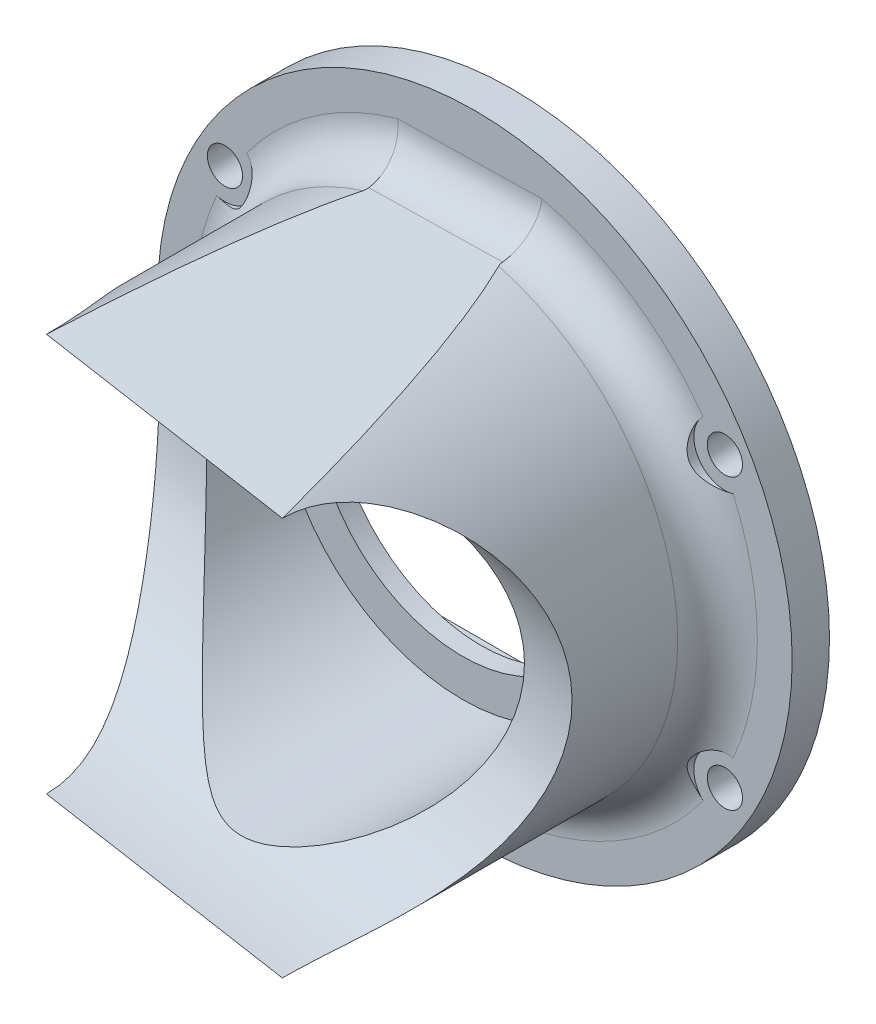
SolidWorks part; units mm, degrees
material "6061-T6 (SS)"
ref_plane "Front Plane" through (0, 0, 0) normal (0, 0, 1) x (1, 0, 0)
ref_plane "Top Plane" through (0, 0, 0) normal (0, 1, 0) x (1, 0, 0)
ref_plane "Right Plane" through (0, 0, 0) normal (1, 0, 0) x (0, 0, -1)
sketch "Sketch1" plane through (0, 0, 0) normal (0, 0, 1) x (1, 0, 0)
  circle A0 centre (0, 0) radius 30.9562
  dimension "D1" = 61.9125
extrude "Boss-Extrude1" add sketch "Sketch1" along normal blind 50.8
sketch "Sketch2" plane through (0, 0, 0) normal (0, 0, -1) x (-1, 0, 0)
  line L1 (-18.3261, -22.2885) -> (18.3261, -22.2885)
  line L2 (-22.2885, -18.3261) -> (-22.2885, 18.3261)
  line L3 (-18.3261, 22.2885) -> (18.3261, 22.2885)
  line L4 (22.2885, -18.3261) -> (22.2885, 18.3261)
  line L5 (-22.2885, -22.2885) -> (22.2885, 22.2885) construction
  line L6 (-22.2885, 22.2885) -> (22.2885, -22.2885) construction
  arc A0 (18.3261, -22.2885) -> (22.2885, -18.3261) centre (18.3261, -18.3261) ccw
  arc A1 (-18.3261, -22.2885) -> (-22.2885, -18.3261) centre (-18.3261, -18.3261) cw
  arc A2 (18.3261, 22.2885) -> (22.2885, 18.3261) centre (18.3261, 18.3261) cw
  arc A3 (-22.2885, 18.3261) -> (-18.3261, 22.2885) centre (-18.3261, 18.3261) cw
  point P0 (0, 0)
  dimension "D3" = 3.9624
  dimension "D1" = 44.577
  dimension "D2" = 44.577
extrude "Cut-Extrude1" cut sketch "Sketch2" against normal blind 3.9624
ref_plane "Plane1" through (30.9562, 0, 0) normal (1, 0, 0) x (0, 0, -1)
sketch "Sketch16" plane through (30.9562, 0, 0) normal (1, 0, 0) x (0, 0, -1)
  line L0 (0, 0) -> (0, -56.7352) construction
ref_plane "Plane4" through (30.2799, 0, 4.5254) normal (0.989, 0, 0.1478) x (0.1478, 0, -0.989)
sketch "Sketch3" plane through (30.9562, 0, 0) normal (0.989, 0, 0.1478) x (0.1478, 0, -0.989)
  line L1 (-48.4676, 25.4) -> (-4.5756, 30.9562)
  line L2 (-4.5756, 30.9562) -> (-67.5176, 30.9562)
  line L3 (-67.5176, 30.9562) -> (-67.5176, -30.9562)
  line L4 (-67.5176, -30.9562) -> (-4.5756, -30.9562)
  line L5 (-4.5756, -30.9562) -> (-48.4676, -25.4)
  arc A0 (-48.4676, -25.4) -> (-48.4676, 25.4) centre (-48.4676, 0) ccw
  dimension "D1" = 50.8
  dimension "D2" = 19.05
  dimension "D3" = 62.942
extrude "Cut-Extrude2" cut sketch "Sketch3" against normal through all and the other way through all
sketch "Sketch4" plane through (0, 0, 3.9624) normal (0, 0, -1) x (-1, 0, 0)
  circle A0 centre (0, 0) radius 19.05
  dimension "D1" = 38.1
extrude "Cut-Extrude3" cut sketch "Sketch4" against normal through all
ref_plane "Plane2" through (0, 0, 50.8) normal (0, 0, 1) x (1, 0, 0)
sketch "Sketch6" plane through (0, 0, 50.8) normal (0, 0, 1) x (1, 0, 0)
  circle A0 centre (0, 0) radius 23.8125
  dimension "D1" = 47.625
extrude "Cut-Extrude4" cut sketch "Sketch6" against normal blind 44.45
sketch "Sketch7" plane through (0, 0, 3.9624) normal (0, 0, -1) x (-1, 0, 0)
  line L1 (-18.2626, -18.2626) -> (18.2626, -18.2626) construction
  line L2 (-18.2626, -18.2626) -> (-18.2626, 18.2626) construction
  line L3 (-18.2626, 18.2626) -> (18.2626, 18.2626) construction
  line L4 (18.2626, -18.2626) -> (18.2626, 18.2626) construction
  line L5 (-18.2626, -18.2626) -> (18.2626, 18.2626) construction
  line L6 (-18.2626, 18.2626) -> (18.2626, -18.2626) construction
  point P0 (0, 0)
  dimension "D1" = 36.5252
  dimension "D2" = 36.5252
hole_wizard "#4-40 Tapped Hole1" positions "Sketch9" profile "Sketch8" tap size "#4-40" standard "Ansi Inch"
sketch "Sketch9" plane through (0, 0, 3.9624) normal (0, 0, -1) x (-1, 0, 0)
  point P0 (-18.2626, 18.2626)
  point P1 (18.2626, 18.2626)
  point P4 (18.2626, -18.2626)
  point P7 (-18.2626, -18.2626)
sketch "Sketch8" plane through (18.2626, 18.2626, 3.9624) normal (1, 0, 0) x (0, 1, 0)
  line L0 (0, 0) -> (0, 8.2992)
  line L1 (0, 8.2992) -> (1.1303, 7.62)
  line L2 (1.1303, 7.62) -> (1.1303, 0)
  line L5 (1.1303, 0) -> (0, 0)
  line L10 (0, 8.2992) -> (-1.1303, 7.62) construction
  line L11 (0, -6.35) -> (0, 107.95) construction
  dimension "Tap Drill Dia." = 2.2606
  dimension "Tap Drill Depth" = 7.62
  dimension "Drill Angle" = 118
cosmetic thread "Hole Thread1" parameters "D1"=5.588, "D2"=2.8448
cosmetic thread "Hole Thread2" parameters "D1"=5.588, "D2"=2.8448
cosmetic thread "Hole Thread3" parameters "D1"=5.588, "D2"=2.8448
cosmetic thread "Hole Thread4" parameters "D1"=5.588, "D2"=2.8448
sketch "Sketch10" plane through (0, 0, 0) normal (0, 0, -1) x (-1, 0, 0)
  line L0 (-17.6955, 25.4) -> (17.6955, 25.4)
  line L1 (-17.6955, -25.4) -> (17.6955, -25.4)
  arc A0 (-17.6955, 25.4) -> (-17.6955, -25.4) centre (0, 0) ccw
  arc A1 (0, 30.9562) -> (0, -30.9562) centre (0, 0) ccw construction
  circle A2 centre (0, 0) radius 40.4813
  arc A3 (17.6955, -25.4) -> (17.6955, 25.4) centre (0, 0) ccw
  dimension "D1" = 9.525
  dimension "D2" = 25.4
extrude "Boss-Extrude3" add sketch "Sketch10" against normal blind 4.7625
sketch "Sketch12" plane through (0, 0, 4.7625) normal (0, 0, 1) x (1, 0, 0)
  circle A0 centre (0, 0) radius 36.83 construction
  dimension "D1" = 73.66
fillet "Fillet1" radius 5.08 4 edges at (30.9562, 0, 4.7625) (-30.9562, 0, 4.7625) (-0.5679, -30.3494, 4.7625) (-0.5679, 30.3494, 4.7625)
hole_wizard "#8 Clearance Hole1" positions "Sketch14" profile "Sketch13" hole size "#8" standard "ANSI Inch"
sketch "Sketch14" plane through (0, 0, 4.7625) normal (0, 0, 1) x (1, 0, 0)
  line L0 (0, 0) -> (0, 40.4813) construction
  line L2 (0, 0) -> (-31.8957, 18.415) construction
  circle A0 centre (0, 0) radius 36.83 construction
  circle A1 centre (0, 0) radius 40.4813 construction
  point P0 (-31.8957, 18.415)
  dimension "D1" = 60
sketch "Sketch13" plane through (-31.8957, 18.415, 4.7625) normal (1, 0, 0) x (0, -1, 0)
  line L0 (0, 0) -> (0, 26.7507)
  line L1 (0, 26.7507) -> (2.2479, 25.4)
  line L2 (2.2479, 25.4) -> (2.2479, 0)
  line L5 (2.2479, 0) -> (0, 0)
  line L10 (0, 26.7507) -> (-2.2479, 25.4) construction
  line L11 (0, -6.35) -> (0, 107.95) construction
  dimension "Hole Dia." = 4.4958
  dimension "Hole Depth" = 25.4
  dimension "Drill Angle" = 118
pattern_circular "CirPattern1" count 2 every 120 about axis through (0, 0, 4.7625) along (0, 0, -1) of "#8 Clearance Hole1"
ref_plane "Plane3" through (0, 0, 9.8425) normal (0, 0, 1) x (1, 0, 0)
mirror "Mirror1" about plane through (0, 0, 0) normal (0, 1, 0) of "CirPattern1", "#8 Clearance Hole1"
sketch "Sketch15" plane through (0, 0, 9.8425) normal (0, 0, 1) x (1, 0, 0)
  circle A0 centre (-31.8957, 18.415) radius 3.9624
  circle A1 centre (31.8957, 18.415) radius 3.9624
  circle A3 centre (31.8957, -18.415) radius 3.9624
  circle A4 centre (-31.8957, -18.415) radius 3.9624
  dimension "D1" = 7.9248
extrude "Cut-Extrude5" cut sketch "Sketch15" against normal up to surface (5.08 mm away) up to face at (-40.4813, 0, 4.7625)
